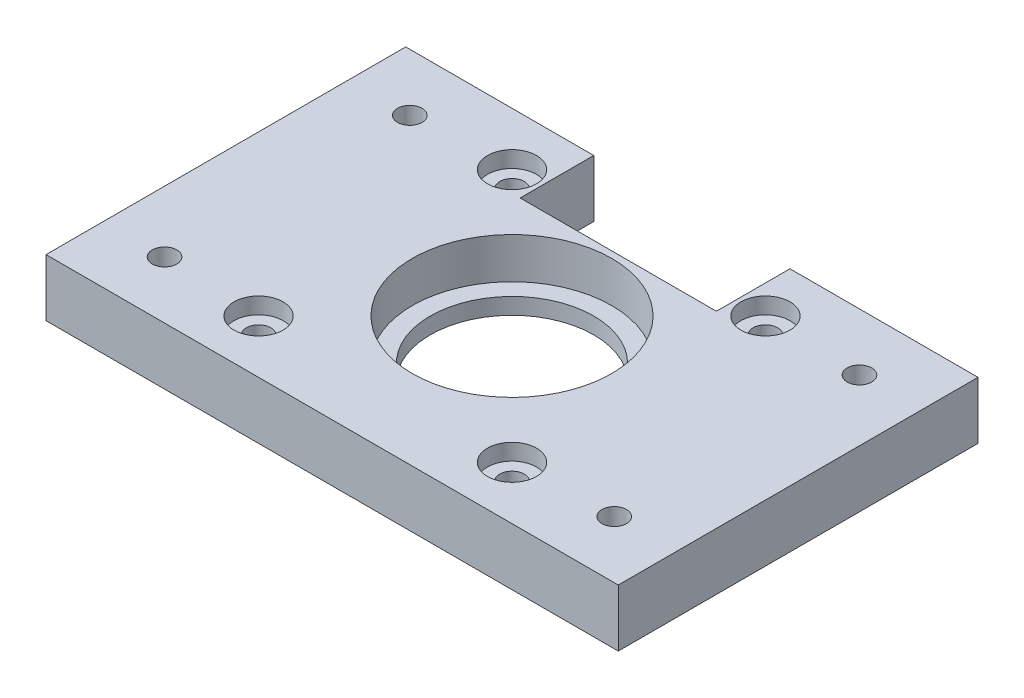
SolidWorks part; units mm, degrees
ref_plane "Front Plane" through (0, 0, 0) normal (0, 0, 1) x (1, 0, 0)
ref_plane "Top Plane" through (0, 0, 0) normal (0, 1, 0) x (1, 0, 0)
ref_plane "Right Plane" through (0, 0, 0) normal (1, 0, 0) x (0, 0, -1)
sketch "Sketch1" plane through (0, 0, 0) normal (0, 1, 0) x (1, 0, 0)
  line L0 (-12, 22) -> (-12, 13)
  line L1 (-35, 22) -> (-12, 22)
  line L2 (-35, 22) -> (-35, -22)
  line L3 (-35, -22) -> (35, -22)
  line L4 (35, 22) -> (35, -22)
  line L5 (12, 22) -> (12, 13)
  line L6 (-12, 13) -> (12, 13)
  line L7 (12, 22) -> (35, 22)
  line L8 (15.5, -15.5) -> (15.5, 15.5) construction
  line L9 (15.5, 15.5) -> (-15.5, 15.5) construction
  line L10 (-15.5, 15.5) -> (-15.5, -15.5) construction
  line L11 (-15.5, -15.5) -> (15.5, -15.5) construction
  circle A0 centre (0, 0) radius 12.2
  circle A1 centre (27.5, -15) radius 1.5
  circle A2 centre (27.5, 15) radius 1.5
  circle A3 centre (-27.5, -15) radius 1.5
  circle A4 centre (-27.5, 15) radius 1.5
  circle A5 centre (15.5, -15.5) radius 1.5
  circle A6 centre (-15.5, -15.5) radius 1.5
  circle A7 centre (15.5, 15.5) radius 1.5
  circle A8 centre (-15.5, 15.5) radius 1.5
  dimension "D5" = 24.4
  dimension "D13" = 3
  dimension "D14" = 3
  dimension "D15" = 3
  dimension "D16" = 3
  dimension "D24" = 3
  dimension "D25" = 3
  dimension "D26" = 3
  dimension "D27" = 3
  dimension "D1" = 44
  dimension "D2" = 70
  dimension "D3" = 35
  dimension "D4" = 22
  dimension "D6" = 23
  dimension "D7" = 23
  dimension "D8" = 9
  dimension "D9" = 7.5
  dimension "D10" = 7.5
  dimension "D11" = 7.5
  dimension "D12" = 7.5
  dimension "D17" = 7
  dimension "D18" = 7
  dimension "D19" = 7
  dimension "D20" = 7
  dimension "D21" = 15.5
  dimension "D22" = 31
  dimension "D23" = 15.5
extrude "Boss-Extrude1" add sketch "Sketch1" along normal blind 7
sketch "Sketch2" plane through (0, 0, 0) normal (0, -1, 0) x (1, 0, 0)
  circle A0 centre (0, 0) radius 12.2
  circle A1 centre (0, 0) radius 10
  dimension "D1" = 20
  dimension "D2" = 24.4
extrude "Boss-Extrude2" add sketch "Sketch2" against normal blind 2
sketch "Sketch3" plane through (0, 0, 0) normal (0, -1, 0) x (1, 0, 0)
  circle A0 centre (-27.5, 15) radius 3
  circle A1 centre (-27.5, -15) radius 3
  circle A2 centre (27.5, 15) radius 3
  circle A3 centre (27.5, -15) radius 3
  dimension "D1" = 6
  dimension "D2" = 6
  dimension "D3" = 6
  dimension "D4" = 6
extrude "Cut-Extrude1" cut sketch "Sketch3" against normal blind 2
sketch "Sketch4" plane through (0, 7, 0) normal (0, 1, 0) x (1, 0, 0)
  circle A0 centre (15.5, -15.5) radius 3
  circle A1 centre (-15.5, -15.5) radius 3
  circle A2 centre (15.5, 15.5) radius 3
  circle A3 centre (-15.5, 15.5) radius 3
  dimension "D1" = 6
  dimension "D2" = 6
  dimension "D3" = 6
  dimension "D4" = 6
extrude "Cut-Extrude2" cut sketch "Sketch4" against normal blind 2
